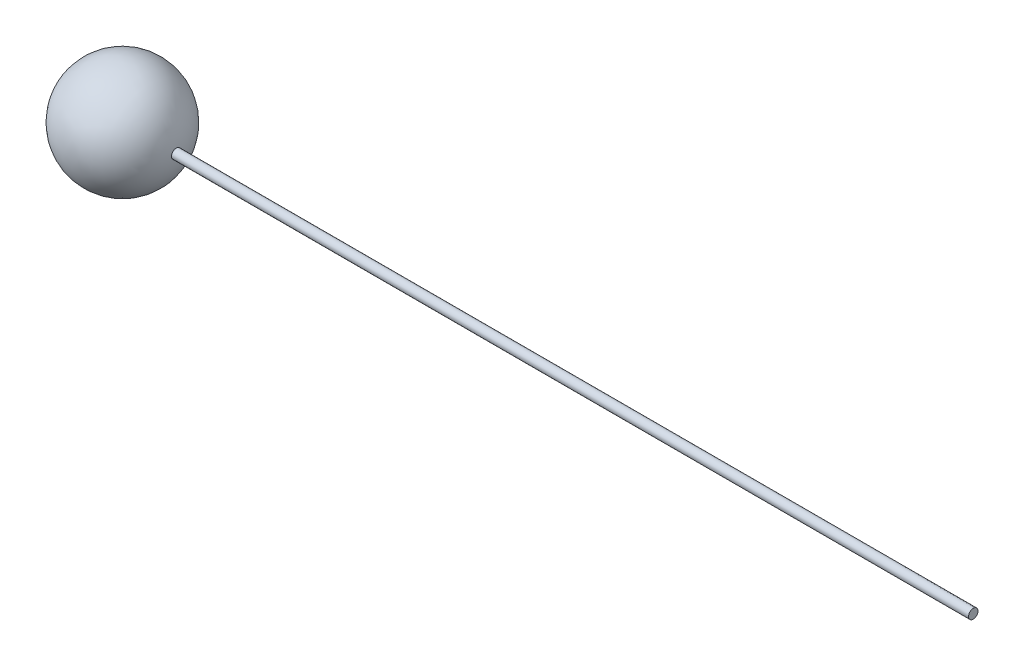
SolidWorks part; units mm, degrees
ref_plane "Front Plane" through (0, 0, 0) normal (0, 0, 1) x (1, 0, 0)
ref_plane "Top Plane" through (0, 0, 0) normal (0, 1, 0) x (1, 0, 0)
ref_plane "Right Plane" through (0, 0, 0) normal (1, 0, 0) x (0, 0, -1)
sketch "Sketch2" plane through (0, 0, 0) normal (0, 0, 1) x (1, 0, 0)
  line L0 (0, 114.3) -> (0, -114.3)
  arc A0 (0, 114.3) -> (0, -114.3) centre (0, 0) ccw
  dimension "D2" = 114.3
  dimension "D1" = 228.6
revolve "Revolve1" add sketch "Sketch2" angle 360 about L0
sketch "Sketch4" plane through (0, 0, 0) normal (0, 0, 1) x (1, 0, 0)
  line L0 (0, 0) -> (1800, 0)
  dimension "D1" = 1800
revolve "Revolve-Thin1" add sketch "Sketch4" angle 360 about L0 wall 10
